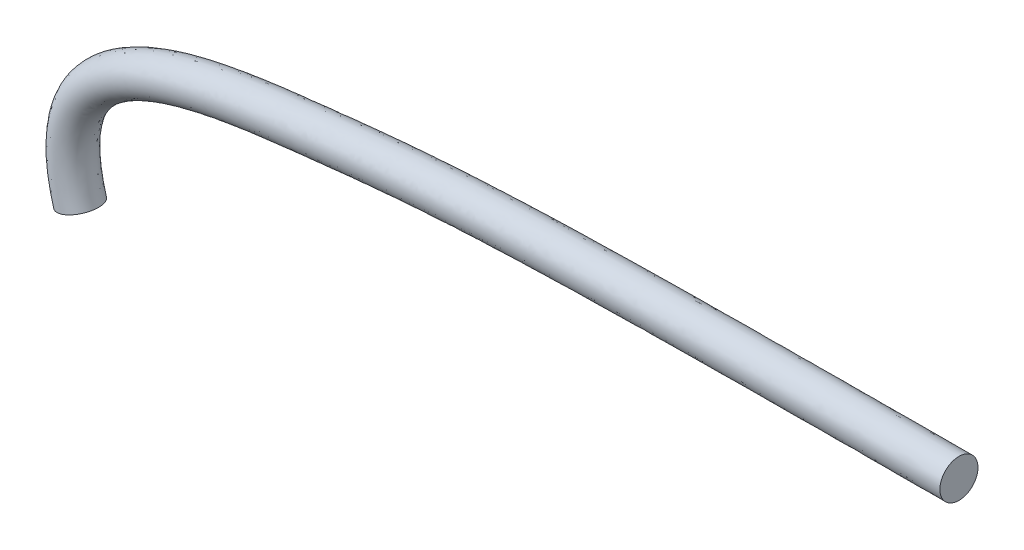
SolidWorks part; units mm, degrees
ref_plane "Front Plane" through (0, 0, 0) normal (0, 0, 1) x (1, 0, 0)
ref_plane "Top Plane" through (0, 0, 0) normal (0, 1, 0) x (1, 0, 0)
ref_plane "Right Plane" through (0, 0, 0) normal (1, 0, 0) x (0, 0, -1)
sketch "Sketch1" plane through (0, 0, 0) normal (0, 1, 0) x (1, 0, 0)
  circle A0 centre (0, 0) radius 15.82
sketch "Sketch2" plane through (0, 0, 0) normal (0, 0, 1) x (1, 0, 0)
  line L0 (15.82, 0) -> (-15.82, 0) construction
  spline S0 degree 3 poles (0, 0) (-35.8774, 121.4853) (260.0651, 158.8553) (368.8206, 166.5185) (730.653, 167.0908) knots 0 0 0 0 0.439736 1 1 1 1
  point P2 (14.8557, 46.8221)
  point P3 (347.5308, 288.0678)
  point P4 (87.4436, 52.2615)
  point P6 (177.4751, 24.5018)
  point P7 (172.9463, 88.4986)
  point P10 (370.8544, 81.7735)
  point P11 (235.7132, 106.432)
  point P12 (575.1959, 101.9794)
  point P13 (521.2547, 104.6213)
  point P14 (1398.0353, 116.7571)
  point P15 (706.4895, 186.898)
  point P16 (1456.1207, 192.3778)
  point P17 (1274.0505, 739.152)
  point P18 (326.7509, 382.403)
  point P19 (3131.1533, 734.7243)
  point P20 (399.7874, 288.0065)
  point P21 (0, 0)
  point P22 (1712.1834, 516.7727)
  point P23 (3281.4399, 508.7459)
  point P24 (1796.4657, 227.8048)
  point P25 (600.4595, 151.5494)
  point P26 (3450.0045, 283.993)
  point P27 (347.527, 257.7901)
  point P28 (298.1099, 276.1015)
  point P29 (694.4145, 303.1282)
  point P30 (1116.7903, 303.1282)
  point P31 (745.9696, 292.6446)
  point P32 (1075.8579, 293.7356)
  point P33 (891.4419, 245.0232)
  point P34 (410.0727, 184.6311)
  point P35 (824.4771, 207.0988)
  point P36 (146.7012, 143.4403)
  point P37 (730.653, 167.0908)
sweep "Sweep1" add path "Sketch2" circular profile diameter 31.7 parameters "D3"=31.7
